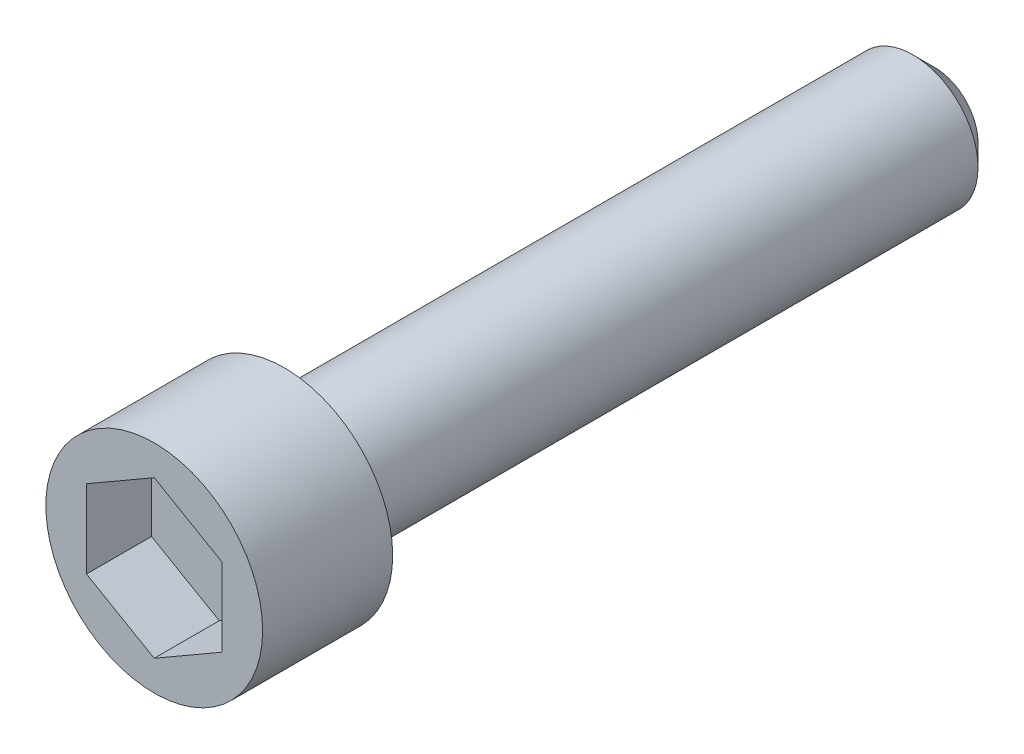
SolidWorks part; units mm, degrees
ref_plane "前视基准面" through (0, 0, 0) normal (0, 0, 1) x (1, 0, 0)
ref_plane "上视基准面" through (0, 0, 0) normal (0, 1, 0) x (1, 0, 0)
ref_plane "右视基准面" through (0, 0, 0) normal (1, 0, 0) x (0, 0, -1)
sketch "草图1" plane through (0, 0, 0) normal (0, 0, 1) x (1, 0, 0)
  circle A0 centre (0, 0) radius 1.5
extrude "凸台-拉伸1" add sketch "草图1" along normal blind 15
sketch "草图2" plane through (0, 0, 15) normal (0, 0, 1) x (1, 0, 0)
  circle A0 centre (0, 0) radius 2.5
extrude "凸台-拉伸2" add sketch "草图2" along normal blind 3
sketch "草图3" plane through (0, 0, 18) normal (0, 0, 1) x (1, 0, 0)
  line L1 (0, 1.8034) -> (-1.5618, 0.9017)
  line L2 (-1.5618, 0.9017) -> (-1.5618, -0.9017)
  line L3 (-1.5618, -0.9017) -> (0, -1.8034)
  line L4 (0, -1.8034) -> (1.5618, -0.9017)
  line L5 (1.5618, -0.9017) -> (1.5618, 0.9017)
  line L6 (1.5618, 0.9017) -> (0, 1.8034)
  circle A0 centre (0, 0) radius 1.5618 construction
extrude "切除-拉伸1" cut sketch "草图3" against normal blind 1.5
chamfer "倒角1" distance 0.5 angle 45 1 edges at (1.5, 0, 0)
